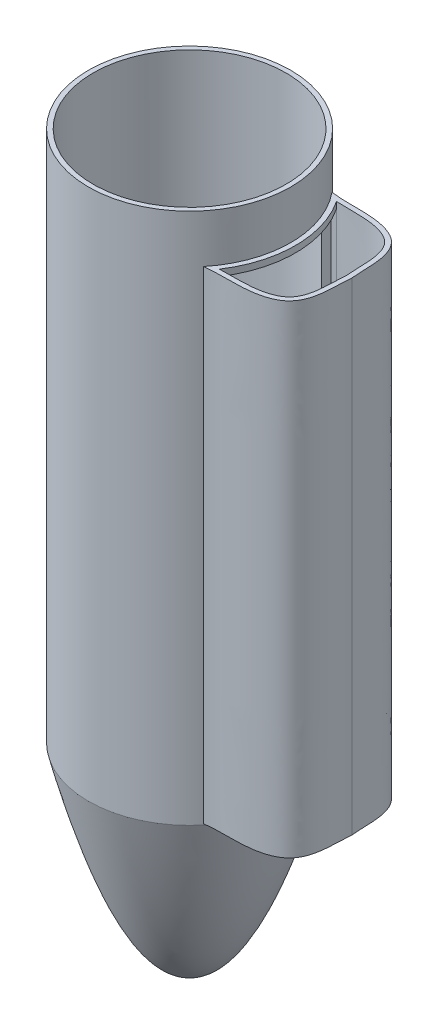
SolidWorks part; units mm, degrees
material "PLA"
ref_plane "Front Plane" through (0, 0, 0) normal (0, 0, 1) x (1, 0, 0)
ref_plane "Top Plane" through (0, 0, 0) normal (0, 1, 0) x (1, 0, 0)
ref_plane "Right Plane" through (0, 0, 0) normal (1, 0, 0) x (0, 0, -1)
curve "Кривая1"
  spline degree 3 poles (0, 0, 0) (0.8371, 0.0409, 0) (2.5342, 0.1239, 0) (5.0631, 0.7897, 0) (7.5839, 1.8455, 0) (10.0965, 3.3287, 0) (12.6026, 5.2245, 0) (15.1041, 7.5351, 0) (17.6028, 10.2593, 0) (20.0998, 13.3975, 0) (22.596, 16.95, 0) (25.0917, 20.9173, 0) (27.5874, 25.2996, 0) (30.0832, 30.0974, 0) (32.5791, 35.3107, 0) (35.0753, 40.94, 0) (37.5717, 46.9852, 0) (40.0684, 53.4466, 0) (42.5653, 60.3242, 0) (45.0624, 67.6181, 0) (47.5598, 75.3284, 0) (50.0572, 83.4551, 0) (52.5552, 91.9981, 0) (55.0518, 100.9581, 0) (57.5549, 110.333, 0) (59.174, 116.7342, 0) (60, 120, 0) knots 0 0 0 0 0.017998 0.036486 0.055916 0.07668 0.0991 0.123431 0.149874 0.178585 0.209686 0.243274 0.279425 0.318199 0.359647 0.403809 0.450718 0.500402 0.552885 0.608187 0.666324 0.727312 0.791164 0.857889 0.927498 1 1 1 1
sketch "Эскиз1" plane through (0, 0, 0) normal (0, 0, 1) x (1, 0, 0)
  line L0 (60, 120) -> (62.9084, 120)
  line L1 (62.9084, 120) -> (62.9084, 119.2644)
  line L2 (0, 124.7775) -> (0, -7.3698) construction
  line L3 (0.1465, -2.9964) -> (0, -2.9964)
  line L4 (0, -2.9964) -> (0, 0)
  spline S0 degree 3 poles (193.6758, -1989.9998) (-56.2345, 67.3253) (-20.6914, -5.9906) (5.0631, 0.7897) (7.5839, 1.8455) (10.0965, 3.3287) (12.6026, 5.2245) (15.1041, 7.5351) (17.6028, 10.2593) (20.0998, 13.3975) (22.596, 16.95) (25.0917, 20.9173) (27.5874, 25.2996) (30.0832, 30.0974) (32.5791, 35.3107) (35.0753, 40.94) (37.5717, 46.9852) (40.0684, 53.4466) (42.5653, 60.3242) (45.0624, 67.6181) (47.5598, 75.3284) (50.0572, 83.4551) (52.5552, 91.9981) (55.0518, 100.9581) (95.8336, 253.7024) (89.4286, 415.4346) (2042.1317, 67.7283) knots -0.513536 -0.513536 -0.513536 -0.513536 0.017998 0.036486 0.055916 0.07668 0.0991 0.123431 0.149874 0.178585 0.209686 0.243274 0.279425 0.318199 0.359647 0.403809 0.450718 0.500402 0.552885 0.608187 0.666324 0.727312 0.791164 0.857889 0.927498 4.193719 4.193719 4.193719 4.193719 only from (0, 0) to (60, 120) construction
  spline S1 degree 3 poles (0, 0) (0.8371, 0.0409) (2.5342, 0.1239) (5.0631, 0.7897) (7.5839, 1.8455) (10.0965, 3.3287) (12.6026, 5.2245) (15.1041, 7.5351) (17.6028, 10.2593) (20.0998, 13.3975) (22.596, 16.95) (25.0917, 20.9173) (27.5874, 25.2996) (30.0832, 30.0974) (32.5791, 35.3107) (35.0753, 40.94) (37.5717, 46.9852) (40.0684, 53.4466) (42.5653, 60.3242) (45.0624, 67.6181) (47.5598, 75.3284) (50.0572, 83.4551) (52.5552, 91.9981) (55.0518, 100.9581) (57.5549, 110.333) (59.174, 116.7342) (60, 120) knots 0 0 0 0 0.017998 0.036486 0.055916 0.07668 0.0991 0.123431 0.149874 0.178585 0.209686 0.243274 0.279425 0.318199 0.359647 0.403809 0.450718 0.500402 0.552885 0.608187 0.666324 0.727312 0.791164 0.857889 0.927498 1 1 1 1
  spline S2 degree 1 poles (0.1465, -2.9964) (62.9084, 119.2644) knots 0 0 1 1 construction
  spline S3 degree 3 poles (0.1465, -2.9964) (0.5291, -2.9777) (1.2657, -2.9417) (2.5388, -2.8337) (3.8874, -2.6042) (5.1522, -2.2776) (6.3573, -1.8832) (7.919, -1.2736) (10.5442, 0.0164) (13.8743, 2.3185) (18.5114, 6.564) (23.3223, 12.501) (28.1674, 20.0735) (32.3932, 27.9084) (36.1787, 35.9075) (39.6321, 44.0207) (43.8881, 54.9488) (48.6839, 68.7637) (53.8531, 85.5004) (57.7898, 99.5282) (60.7711, 110.809) (62.1951, 116.4443) (62.9084, 119.2644) knots 0 0 0 0 0.007812 0.015625 0.023438 0.03125 0.039062 0.046875 0.0625 0.09375 0.125 0.1875 0.25 0.3125 0.375 0.4375 0.5 0.625 0.75 0.875 0.9375 1 1 1 1
  dimension "D1" = 3
revolve "Повернуть1" add sketch "Эскиз1" angle 360 about L2
sketch "Эскиз2" plane through (0, 120, 0) normal (0, 1, 0) x (1, 0, 0)
  circle A0 centre (0, 0) radius 62.9084 construction
  circle A1 centre (0, 0) radius 60 construction
  circle A2 centre (0, 0) radius 62.9084
  circle A3 centre (0, 0) radius 60
extrude "Бобышка-Вытянуть1" add sketch "Эскиз2" along normal blind 330
ref_plane "Плоскость1" through (100, 0, 0) normal (1, 0, 0) x (0, 0, -1)
sketch "Эскиз4" plane through (0, 0, 0) normal (0, 1, 0) x (1, 0, 0)
  line L0 (-77.0126, 0) -> (200.5833, 0) construction
  line L1 (62.9084, 0) -> (62.9084, 119.3765) construction
  line L2 (62.9084, 0) -> (62.9084, -112.7672) construction
  line L3 (48.5538, 40) -> (100.9084, 0) construction
  line L4 (48.5538, -40) -> (100.9084, -40) construction
  line L6 (48.5538, 40) -> (100.9084, 40) construction
  line L7 (100.9084, -40) -> (100.9084, 40) construction
  circle A0 centre (0, 0) radius 62.9084 construction
  arc A1 (48.5538, -40) -> (48.5538, 40) centre (0, 0) ccw
  arc A2 (54.9244, -36.4312) -> (54.9244, 36.4312) centre (0, 0) ccw
  spline S0 degree 3 poles (48.5538, 40) (60.8281, 38.1775) (77.9947, 41.5797) (92.5804, 33.2026) (101.7497, 23.2693) (99.8604, 8.6477) (100.9084, 0) knots 0 0 0 0 0.504739 0.556934 0.625207 1 1 1 1
  spline S1 degree 3 poles (48.5538, -40) (60.8281, -38.1775) (77.9947, -41.5797) (92.5804, -33.2026) (101.7497, -23.2693) (99.8604, -8.6477) (100.9084, 0) knots 0 0 0 0 0.504739 0.556934 0.625207 1 1 1 1
  spline S2 degree 1 poles (54.9244, 36.4312) (97.8881, 0) knots 0 0 1 1 construction
  spline S3 degree 1 poles (54.9244, -36.4312) (97.8881, 0) knots 0 0 1 1 construction
  spline S4 degree 3 poles (54.9244, 36.4312) (56.4643, 36.3663) (59.5388, 36.3057) (65.7536, 36.2869) (71.9068, 36.1822) (77.7668, 35.5494) (81.9549, 34.7137) (85.8676, 33.4265) (88.9258, 31.9034) (90.8961, 30.4347) (92.2399, 29.0972) (93.4053, 27.5896) (94.6962, 25.4013) (95.8922, 22.2985) (96.7658, 18.0976) (97.2143, 13.5909) (97.4083, 8.9581) (97.5179, 5.1354) (97.6819, 2.1568) (97.807, 0.7219) (97.8881, 0) knots 0.085618 0.085618 0.085618 0.085618 0.142466 0.199315 0.313011 0.369859 0.426707 0.483556 0.540404 0.568828 0.597252 0.625676 0.6541 0.710949 0.767797 0.824645 0.881493 0.938341 0.966765 0.99519 0.99519 0.99519 0.99519
  spline S5 degree 3 poles (97.8881, 0) (97.807, -0.7219) (97.6819, -2.1568) (97.5179, -5.1354) (97.4083, -8.9581) (97.2143, -13.5909) (96.7658, -18.0976) (95.8922, -22.2985) (94.6962, -25.4013) (93.4053, -27.5896) (92.2399, -29.0972) (90.8961, -30.4347) (88.9258, -31.9034) (85.8676, -33.4265) (81.9549, -34.7137) (77.7668, -35.5494) (71.9068, -36.1822) (65.7536, -36.2869) (59.5388, -36.3057) (56.4643, -36.3663) (54.9244, -36.4312) knots 0.085618 0.085618 0.085618 0.085618 0.114042 0.142466 0.199315 0.256163 0.313011 0.369859 0.426707 0.455132 0.483556 0.51198 0.540404 0.597252 0.6541 0.710949 0.767797 0.881493 0.938341 0.99519 0.99519 0.99519 0.99519
  point P8 (74.7311, 20)
  point P13 (48.5538, 40)
  point P14 (48.5538, -40)
  point P15 (100.9084, 0)
  point P16 (48.5538, 40)
  point P17 (48.5538, -40)
  point P18 (100.9084, 0)
  point P21 (0, 0)
  point P22 (92.0964, 33.2675)
  point P23 (0, 0)
  point P28 (88.5156, 35.4207)
  point P29 (74.135, 38.9263)
  point P30 (95.8351, 29.2809)
  point P35 (99.3469, 20.3)
  dimension "D2" = 38
  dimension "D1" = 80
  dimension "D3" = 3
extrude "Бобышка-Вытянуть4" add sketch "Эскиз4" along normal blind 300 from offset 120
sketch "Эскиз5" plane through (100, 0, 0) normal (1, 0, 0) x (0, 0, -1)
  line L0 (-40, 120) -> (40, 120) construction
  line L1 (-40, 420) -> (-40, 120) construction
  line L2 (40, 420) -> (-40, 420) construction
  line L3 (40, 420) -> (40, 120) construction
  line L4 (-40, 120) -> (40, 120)
  line L5 (-40, 420) -> (-40, 120)
  line L6 (40, 420) -> (-40, 420)
  line L7 (40, 420) -> (40, 120)
  line L8 (-36, 124) -> (36, 124)
  line L9 (36, 416) -> (36, 124)
  line L10 (36, 416) -> (-36, 416)
  line L11 (-36, 416) -> (-36, 124)
  dimension "D1" = 4
extrude "Вырез-Вытянуть2" cut sketch "Эскиз5" against normal blind 18 from offset 30 contours L10 L11 L8 L9
